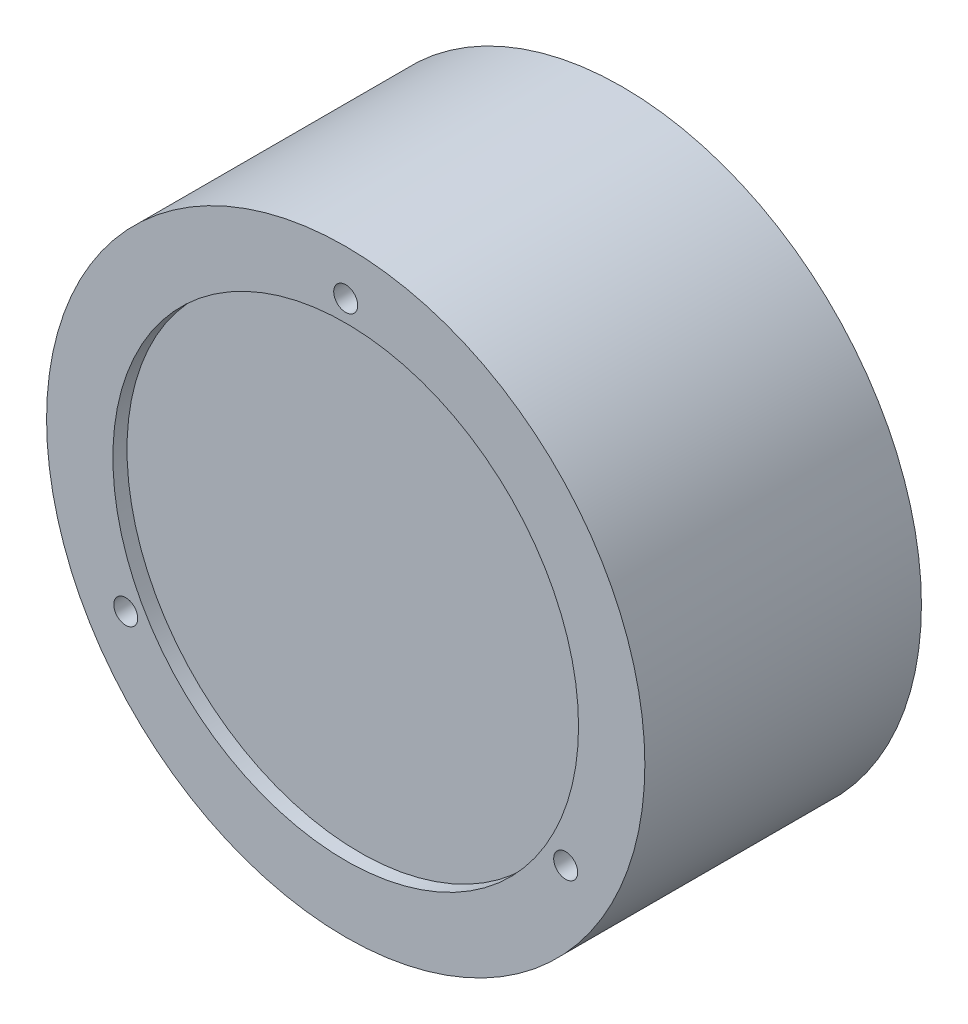
SolidWorks part; units mm, degrees
material "Q235A"
ref_plane "前视" through (0, 0, 0) normal (0, 0, 1) x (1, 0, 0)
ref_plane "上视" through (0, 0, 0) normal (0, 1, 0) x (1, 0, 0)
ref_plane "右视" through (0, 0, 0) normal (1, 0, 0) x (0, 0, -1)
sketch "草图1" plane through (0, 0, 0) normal (0, 0, 1) x (1, 0, 0)
  circle A0 centre (0, 0) radius 106
  dimension "D1" = 212
extrude "凸台-拉伸1" add sketch "草图1" along normal blind 98
sketch "草图2" plane through (0, 0, 98) normal (0, 0, 1) x (1, 0, 0)
  circle A0 centre (0, 0) radius 82.5
  dimension "D1" = 165
extrude "切除-拉伸1" cut sketch "草图2" against normal blind 5
hole_wizard "M10 螺纹孔1" positions "草图4" profile "草图3" tap size "M10" standard "GB"
sketch "草图4" plane through (0, 0, 98) normal (0, 0, 1) x (1, 0, 0)
  line L0 (50, 0) -> (-50, 0) construction
  point P0 (0, 90)
  dimension "D1" = 90
sketch "草图3" plane through (0, 90, 98) normal (1, 0, 0) x (0, -1, 0)
  line L0 (0, 0) -> (0, 32.5537)
  line L1 (0, 32.5537) -> (4.25, 30)
  line L2 (4.25, 30) -> (4.25, 0)
  line L5 (4.25, 0) -> (0, 0)
  line L10 (0, 32.5537) -> (-4.25, 30) construction
  line L11 (0, -6.35) -> (0, 107.95) construction
  dimension "螺纹孔钻头直径" = 8.5
  dimension "螺纹孔钻头深度" = 30
  dimension "导头角度" = 118
cosmetic thread "孔螺蚊线1" parameters "D1"=20, "D2"=10
pattern_circular "阵列(圆周)1" count 3 over 360 about axis through (0, 0, 0) along (0, 0, 1) of "M10 螺纹孔1"
hole_wizard "M10 螺纹孔2" positions "草图6" profile "草图5" tap size "M10" standard "GB"
sketch "草图6" plane through (0, 0, 0) normal (0, 0, -1) x (-1, 0, 0)
  line L0 (50, 0) -> (-50, 0) construction
  point P0 (0, 100)
  point P2 (0, 75)
  dimension "D1" = 25
  dimension "D2" = 75
sketch "草图5" plane through (0, 100, 0) normal (1, 0, 0) x (0, 1, 0)
  line L0 (0, 0) -> (0, 27.0537)
  line L1 (0, 27.0537) -> (4.25, 24.5)
  line L2 (4.25, 24.5) -> (4.25, 0)
  line L5 (4.25, 0) -> (0, 0)
  line L10 (0, 27.0537) -> (-4.25, 24.5) construction
  line L11 (0, -6.35) -> (0, 107.95) construction
  dimension "螺纹孔钻头直径" = 8.5
  dimension "螺纹孔钻头深度" = 24.5
  dimension "导头角度" = 118
cosmetic thread "孔螺蚊线2" parameters "D1"=20, "D2"=10
cosmetic thread "孔螺蚊线3" parameters "D1"=20, "D2"=10
pattern_circular "阵列(圆周)2" count 3 over 360 about axis through (0, 0, 0) along (0, 0, 1) of "M10 螺纹孔2"
